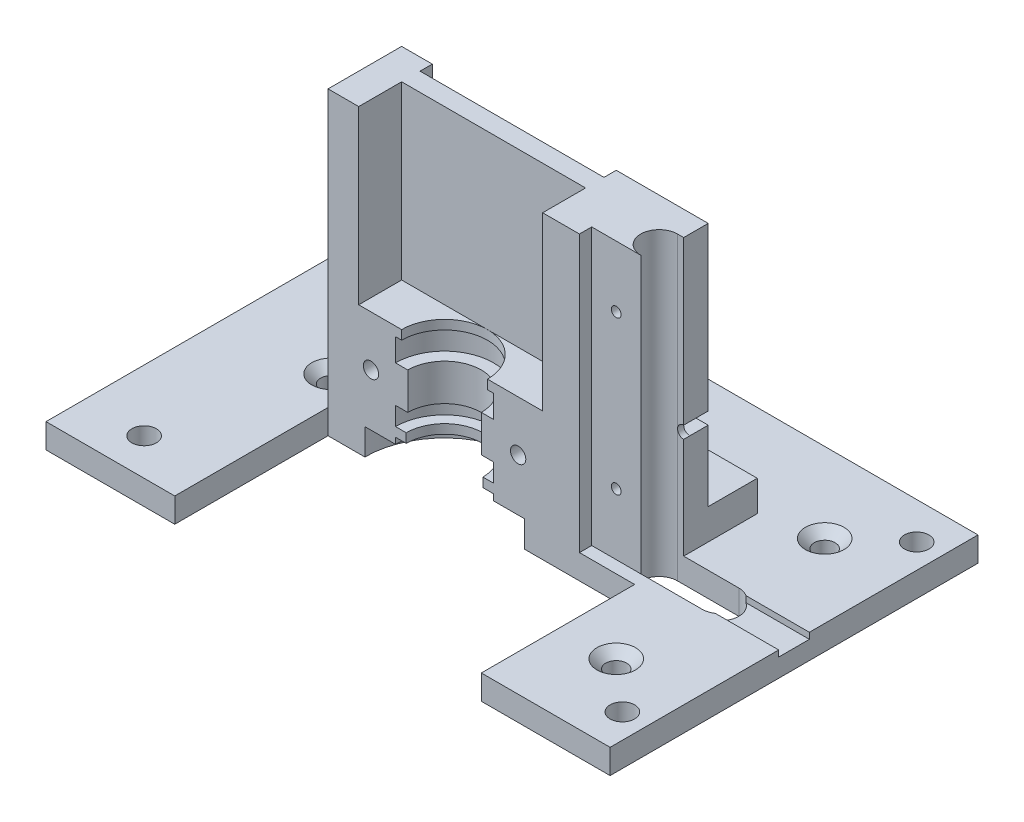
SolidWorks part; units mm, degrees
ref_plane "Front Plane" through (0, 0, 0) normal (0, 0, 1) x (1, 0, 0)
ref_plane "Top Plane" through (0, 0, 0) normal (0, 1, 0) x (1, 0, 0)
ref_plane "Right Plane" through (0, 0, 0) normal (1, 0, 0) x (0, 0, -1)
sketch "Sketch1" plane through (0, 0, 0) normal (0, 1, 0) x (1, 0, 0)
  line L0 (25, -30) -> (46, -30)
  line L1 (-46, -30) -> (-25, -30)
  line L2 (-46, -30) -> (-46, 30)
  line L3 (-46, 30) -> (-25, 30)
  line L4 (46, -30) -> (46, 30)
  line L5 (-46, -30) -> (46, 30) construction
  line L6 (-46, 30) -> (46, -30) construction
  line L8 (-25, -30) -> (-25, -5)
  line L9 (-25, -5) -> (25, -5)
  line L10 (25, -30) -> (25, -5)
  line L11 (-9.5, 30) -> (46, 30)
  line L13 (-25, 30) -> (-25, 25)
  line L14 (-25, 25) -> (-9.5, 25)
  line L15 (-9.5, 30) -> (-9.5, 25)
  point P0 (0, 0)
  dimension "D1" = 60
  dimension "D2" = 92
  dimension "D3" = 25
  dimension "D4" = 50
  dimension "D5" = 21
  dimension "D6" = 15.5
  dimension "D7" = 5
  dimension "D8" = 21
extrude "Boss-Extrude1" add sketch "Sketch1" along normal blind 4
sketch "Sketch2" plane through (0, 4, 0) normal (0, 1, 0) x (1, 0, 0)
  line L1 (-25, -5) -> (25, -5)
  line L2 (-25, -5) -> (-25, 15)
  line L3 (-25, 15) -> (25, 15)
  line L4 (25, -5) -> (25, 15)
  dimension "D1" = 20
  dimension "D2" = 50
extrude "Boss-Extrude2" add sketch "Sketch2" along normal blind 5
sketch "Sketch3" plane through (0, 9, 0) normal (0, 1, 0) x (1, 0, 0)
  line L1 (-25, -5) -> (25, -5)
  line L2 (-25, -5) -> (-25, 7)
  line L3 (-25, 7) -> (25, 7)
  line L4 (25, -5) -> (25, 7)
  dimension "D1" = 12
  dimension "D2" = 50
extrude "Boss-Extrude3" add sketch "Sketch3" along normal blind 40
sketch "Sketch4" plane through (0, 0, -7) normal (0, 0, -1) x (-1, 0, 0)
  line L0 (-25, 49) -> (25, 49) construction
  line L1 (-10, 49) -> (20, 49)
  line L2 (-15, 44) -> (-15, 14)
  line L3 (-10, 9) -> (20, 9)
  line L4 (25, 44) -> (25, 14)
  line L5 (-15, 49) -> (25, 9) construction
  line L6 (-15, 9) -> (25, 49) construction
  line L7 (25, 49) -> (25, 9) construction
  line L11 (-15, 44) -> (-10, 44)
  line L12 (-10, 49) -> (-10, 44)
  line L15 (25, 44) -> (20, 44)
  line L16 (20, 49) -> (20, 44)
  line L19 (-15, 14) -> (-10, 14)
  line L20 (-10, 9) -> (-10, 14)
  line L23 (25, 14) -> (20, 14)
  line L24 (20, 9) -> (20, 14)
  point P0 (5, 29)
  dimension "D1" = 20
  dimension "D2" = 20
  dimension "D3" = 40
  dimension "D4" = 40
  dimension "D5" = 5
  dimension "D6" = 5
  dimension "D7" = 5
  dimension "D8" = 5
  dimension "D9" = 5
  dimension "D10" = 5
  dimension "D11" = 5
  dimension "D12" = 5
  dimension "D13" = 5
  dimension "D14" = 5
  dimension "D15" = 15
  dimension "D16" = 15
  dimension "D17" = 30
  dimension "D18" = 30
extrude "Cut-Extrude1" cut sketch "Sketch4" against normal blind 2
sketch "Sketch5" plane through (0, 0, 5) normal (0, 0, 1) x (1, 0, 0)
  line L0 (-25, 49) -> (25, 49) construction
  line L1 (-20, 49) -> (10, 49)
  line L2 (-20, 49) -> (-20, 21)
  line L3 (-20, 21) -> (10, 21)
  line L4 (10, 49) -> (10, 21)
  line L5 (-25, 49) -> (-25, 4) construction
  dimension "D1" = 28
  dimension "D2" = 30
  dimension "D3" = 5
extrude "Cut-Extrude2" cut sketch "Sketch5" against normal blind 7
ref_plane "Plane1" through (-6, 0, 0) normal (-1, 0, 0) x (0, 0, 1)
sketch "Sketch6" plane through (-6, 0, 0) normal (-1, 0, 0) x (0, 0, 1)
  line L0 (5, 0) -> (5, 21) construction
  line L1 (-30, 0) -> (30, 0) construction
  line L2 (5, 49) -> (5, 4) construction
  line L3 (5, 0) -> (5, 21)
  line L4 (5, 21) -> (-2, 21)
  line L5 (-2, 21) -> (-2, 19.5)
  line L6 (-2, 19.5) -> (-3, 19.5)
  line L7 (-3, 19.5) -> (-3, 15.8)
  line L8 (-3, 15.8) -> (-1, 15.8)
  line L9 (-1, 15.8) -> (-1, 9.8)
  line L10 (-1, 9.8) -> (-3, 9.8)
  line L11 (-3, 9.8) -> (-3, 6.8)
  line L12 (-3, 6.8) -> (-1.25, 6.8)
  line L13 (-1.25, 6.8) -> (-1.25, 5.3)
  line L14 (-1.25, 5.3) -> (-3, 5.3)
  line L15 (-3, 5.3) -> (-3, 4.3)
  line L16 (-3, 4.3) -> (-8, 4.3)
  line L17 (-8, 4.3) -> (-8, 0)
  line L18 (-8, 0) -> (5, 0)
  dimension "D1" = 21
  dimension "D2" = 5
  dimension "D3" = 7
  dimension "D4" = 1.5
  dimension "D5" = 1
  dimension "D6" = 3.7
  dimension "D7" = 2
  dimension "D8" = 6
  dimension "D9" = 2
  dimension "D10" = 3
  dimension "D11" = 1.75
  dimension "D12" = 1.5
  dimension "D13" = 1.75
  dimension "D14" = 1
  dimension "D15" = 5
revolve "Cut-Revolve1" cut sketch "Sketch6" angle 360 about L0
sketch "Sketch7" plane through (0, 0, 0) normal (0, -1, 0) x (1, 0, 0)
  line L0 (46, 30) -> (34, 30) construction
  line L1 (25, 30) -> (46, 30) construction
  line L2 (34, 30) -> (34, 0) construction
  line L3 (34, 0) -> (24, 0) construction
  line L4 (34, -3) -> (24, -3)
  line L5 (34, 3) -> (24, 3)
  arc A0 (34, -3) -> (34, 3) centre (34, 0) ccw
  arc A1 (24, 3) -> (24, -3) centre (24, 0) ccw
  point P5 (29, 0)
  dimension "D4" = 3
  dimension "D5" = 5
  dimension "D1" = 12
  dimension "D2" = 30
  dimension "D3" = 10
extrude "Cut-Extrude3" cut sketch "Sketch7" against normal blind 55
sketch "Sketch8" plane through (0, 0, 5) normal (0, 0, 1) x (1, 0, 0)
  line L1 (25, 49) -> (16, 49)
  line L2 (25, 49) -> (25, 4)
  line L3 (25, 4) -> (16, 4)
  line L4 (16, 49) -> (16, 4)
  dimension "D1" = 45
  dimension "D2" = 9
extrude "Cut-Extrude4" cut sketch "Sketch8" against normal blind 2
sketch "Sketch9" plane through (0, 0, -7) normal (0, 0, -1) x (-1, 0, 0)
  line L0 (-25, 49) -> (-25, 9) construction
  line L1 (-25, 22.5) -> (25, 22.5)
  line L2 (-25, 22.5) -> (-25, 20.5)
  line L3 (-25, 20.5) -> (25, 20.5)
  line L4 (25, 22.5) -> (25, 20.5)
  line L5 (25, 14) -> (25, 44) construction
  line L6 (-46, 4) -> (9.5, 4) construction
  dimension "D1" = 16.5
  dimension "D2" = 2
extrude "Cut-Extrude5" cut sketch "Sketch9" against normal blind 3
sketch "Sketch10" plane through (0, 0, -4) normal (0, 0, -1) x (-1, 0, 0)
  line L0 (-25, 22.5) -> (-25, 20.5) construction
  circle A0 centre (-25, 21.5) radius 1
  dimension "D1" = 2
extrude "Cut-Extrude6" cut sketch "Sketch10" against normal blind 2
sketch "Sketch11" plane through (0, 4, 0) normal (0, 1, 0) x (1, 0, 0)
  line L0 (34, 0) -> (46, 0) construction
  line L1 (46, -30) -> (46, 30) construction
  line L2 (46, 0) -> (46, 2.5) construction
  line L4 (46, 2.5) -> (31, 2.5)
  line L5 (46, 2.5) -> (46, -2.5)
  line L6 (46, -2.5) -> (31, -2.5)
  line L7 (31, 2.5) -> (31, -2.5)
  dimension "D1" = 2.5
  dimension "D2" = 5
  dimension "D3" = 15
extrude "Cut-Extrude7" cut sketch "Sketch11" against normal blind 1
sketch "Sketch12" plane through (0, 9, 0) normal (0, 1, 0) x (1, 0, 0)
  line L1 (-19.25, 14.25) -> (9.25, 14.25)
  line L2 (-19.25, 14.25) -> (-19.25, 5.75)
  line L3 (-19.25, 5.75) -> (9.25, 5.75)
  line L4 (9.25, 14.25) -> (9.25, 5.75)
  line L6 (10, 5) -> (-20, 5) construction
  dimension "D1" = 28.5
  dimension "D2" = 8.5
  dimension "D3" = 0.75
  dimension "D4" = 0.75
extrude "Boss-Extrude4" add sketch "Sketch12" along normal blind 2
sketch "Sketch13" plane through (0, 11, 0) normal (0, 1, 0) x (1, 0, 0)
  line L7 (-19.25, 14.25) -> (-19.25, 5.75) construction
  line L8 (-18.75, 13.75) -> (8.25, 13.75)
  line L9 (-18.75, 13.75) -> (-18.75, 5.75)
  line L10 (-18.75, 5.75) -> (8.25, 5.75)
  line L11 (8.25, 13.75) -> (8.25, 5.75)
  line L12 (9.25, 14.25) -> (-19.25, 14.25) construction
  dimension "D1" = 27
  dimension "D2" = 0.5
  dimension "D3" = 0.5
  dimension "D4" = 8
extrude "Cut-Extrude8" cut sketch "Sketch13" against normal blind 15
sketch "Sketch18" plane through (8.25, 0, 0) normal (-1, 0, 0) x (0, 0, 1)
  line L3 (-7, 4) -> (-7, 0)
  line L12 (-7.75, 5) -> (-7.75, 4)
  line L13 (-7.75, 4) -> (-7, 4)
  line L14 (-30, 0) -> (30, 0) construction
  line L15 (-7, 0) -> (-5.75, 0)
  line L16 (-5.75, 0) -> (-5.75, 9) construction
  line L17 (-5.75, 9) -> (-7.75, 5)
  line L18 (-5.75, 9) -> (-5.75, 0)
  dimension "D1" = 4
  dimension "D2" = 2
  dimension "D4" = 0.75
  dimension "D5" = 4
extrude "Boss-Extrude5" add sketch "Sketch18" along direction (1, 0, 0) on the side of the normal blind 27 contours L15 L18 L17 L12 L13 L3
sketch "Sketch31" plane through (0, 0, 0) normal (0, -1, 0) x (1, 0, 0)
  line L1 (-18.75, -13.75) -> (8.25, -13.75)
  line L2 (-18.75, -13.75) -> (-18.75, -14.5)
  line L3 (-18.75, -14.5) -> (8.25, -14.5)
  line L4 (8.25, -13.75) -> (8.25, -14.5)
  dimension "D1" = 0.75
  dimension "D2" = 27
extrude "Cut-Extrude26" cut sketch "Sketch31" against normal blind 4
ref_plane "Plane3" through (-15, 0, 0) normal (-1, 0, 0) x (0, 0, 1)
sketch "Sketch20" plane through (-15, 0, 0) normal (-1, 0, 0) x (0, 0, 1)
  line L0 (30, 0) -> (-7, 0) construction
  line L1 (-30, 0) -> (30, 0) construction
  line L2 (-7, 0) -> (-7, 2) construction
  line L3 (-7, 0) -> (-14.5, 0) construction
  line L4 (-14.5, 0) -> (-14.5, 2) construction
  line L5 (-14.5, 3) -> (-14.5, 2)
  line L14 (-14.5, 2) -> (-13.5, 2)
  line L15 (-7, 3) -> (-7, 2)
  line L16 (-7, 2) -> (-8, 2)
  line L17 (-7, 2) -> (-14.5, 2) construction
  arc A1 (-13.5, 2) -> (-14.5, 3) centre (-14.5, 2) ccw
  arc A2 (-7, 3) -> (-8, 2) centre (-7, 2) ccw
  dimension "D5" = 2
  dimension "D6" = 2
  dimension "D1" = 37
  dimension "D2" = 2
  dimension "D3" = 7.5
  dimension "D4" = 2
revolve "Revolve1" add sketch "Sketch20" angle 360 about L17
ref_plane "Plane4" through (3, 0, 0) normal (-1, 0, 0) x (0, 0, 1)
sketch "Sketch21" plane through (3, 0, 0) normal (-1, 0, 0) x (0, 0, 1)
  line L0 (30, 0) -> (-7, 0) construction
  line L1 (-30, 0) -> (30, 0) construction
  line L2 (-7, 0) -> (-7, 2) construction
  line L3 (-7, 0) -> (-14.5, 0) construction
  line L4 (-14.5, 0) -> (-14.5, 2) construction
  line L5 (-14.5, 3) -> (-14.5, 2)
  line L6 (-14.5, 2) -> (-13.5, 2)
  line L7 (-7, 3) -> (-7, 2)
  line L8 (-7, 2) -> (-8, 2)
  line L9 (-14.5, 2) -> (-7, 2) construction
  arc A0 (-7, 3) -> (-8, 2) centre (-7, 2) ccw
  arc A1 (-13.5, 2) -> (-14.5, 3) centre (-14.5, 2) ccw
  dimension "D5" = 2
  dimension "D6" = 2
  dimension "D1" = 37
  dimension "D2" = 2
  dimension "D3" = 7.5
  dimension "D4" = 2
revolve "Revolve2" add sketch "Sketch21" angle 360 about L9
sketch "Sketch22" plane through (0, 0, 5) normal (0, 0, 1) x (1, 0, 0)
  line L0 (-25, 0) -> (-19, 0) construction
  line L2 (-25, 49) -> (-25, 4) construction
  line L3 (7, 0) -> (25, 0) construction
  circle A0 centre (6, 12.8) radius 1
  circle A1 centre (-18, 12.8) radius 1
  dimension "D3" = 2
  dimension "D4" = 2
  dimension "D1" = 12.8
  dimension "D5" = 7
  dimension "D2" = 24
  dimension "D6" = 12.8
hole_wizard "M3 Tapped Hole1" positions "3DSketch1" profile "Sketch23" tap size "M3" standard "DIN"
sketch3d "3DSketch1"
  point P0 (-18, 12.8, 5)
  point P3 (6, 12.8, 5)
cosmetic thread "Hole Thread1" parameters "D1"=3.05, "D2"=3
cosmetic thread "Hole Thread2" parameters "D1"=3.05, "D2"=3
sketch "Sketch23" plane through (-18, 12.8, 5) normal (1, 0, 0) x (0, -1, 0)
  line L0 (0, 0) -> (0, 7.7511)
  line L1 (0, 7.7511) -> (1.25, 7)
  line L2 (1.25, 7) -> (1.25, 0)
  line L5 (1.25, 0) -> (0, 0)
  line L10 (0, 7.7511) -> (-1.25, 7) construction
  line L11 (0, -6.35) -> (0, 107.95) construction
  dimension "Tap Drill Dia." = 2.5
  dimension "Tap Drill Depth" = 7
  dimension "Drill Angle" = 118
sketch "Sketch24" plane through (0, 0, 3) normal (0, 0, 1) x (1, 0, 0)
  line L0 (16, 49) -> (20, 49) construction
  line L1 (24, 49) -> (16, 49) construction
  line L2 (20, 49) -> (20, 39) construction
  line L3 (20, 39) -> (20, 14) construction
  dimension "D1" = 4
  dimension "D2" = 10
  dimension "D3" = 25
hole_wizard "M2 Tapped Hole1" positions "3DSketch2" profile "Sketch25" tap size "M2" standard "DIN" end condition through all
sketch3d "3DSketch2"
  point P0 (20, 39, 3)
  point P3 (20, 14, 3)
sketch "Sketch25" plane through (20, 39, 3) normal (1, 0, 0) x (0, -1, 0)
  line L0 (0, 0) -> (0, 33)
  line L1 (0, 33) -> (0.8, 33)
  line L2 (0.8, 33) -> (0.8, 0)
  line L5 (0.8, 0) -> (0, 0)
  line L11 (0, -6.35) -> (0, 107.95) construction
  dimension "Thru Tap Drill Dia." = 1.6
  dimension "Thru Tap Drill Depth" = 33
cosmetic thread "Hole Thread3" parameters "D2"=2
cosmetic thread "Hole Thread4" parameters "D2"=2
sketch "Sketch26" plane through (0, 4, 0) normal (0, 1, 0) x (1, 0, 0)
  line L0 (-25, 30) -> (-46, 30) construction
  line L1 (-46, 30) -> (-46, -30) construction
  circle A0 centre (-36, 24) radius 2
  dimension "D1" = 6
  dimension "D2" = 10
  dimension "D3" = 4
extrude "Cut-Extrude25" cut sketch "Sketch26" against normal blind 5
pattern_linear "LPattern2" count 2 spacing 78 along (1, 0, 0) count 2 spacing 48 along (0, 0, 1) of "Cut-Extrude25"
sketch "Sketch27" plane through (0, 4, 0) normal (0, 1, 0) x (1, 0, 0)
  line L0 (-46, 0) -> (-29.5, 0) construction
  line L1 (-46, 30) -> (-46, -30) construction
  line L2 (-25, 30) -> (-46, 30) construction
  line L3 (46, 17) -> (34, 17) construction
  line L4 (46, 2.5) -> (46, 30) construction
  line L5 (46, 30) -> (-9.5, 30) construction
  line L6 (46, -17) -> (34, -17) construction
  line L7 (46, -30) -> (46, -2.5) construction
  dimension "D1" = 16.5
  dimension "D2" = 30
  dimension "D3" = 12
  dimension "D4" = 13
  dimension "D5" = 12
  dimension "D6" = 34
hole_wizard "CSK for M3 Countersunk Flat Head Screw1" positions "3DSketch3" profile "Sketch28" countersink size "M3" standard "DIN" end condition through all
sketch3d "3DSketch3"
  point P0 (-29.5, 4, 0)
  point P3 (34, 4, -17)
  point P6 (34, 4, 17)
sketch "Sketch28" plane through (-29.5, 4, 0) normal (1, 0, 0) x (0, 0, 1)
  line L0 (0, 0) -> (0, 4)
  line L1 (0, 4) -> (1.7, 4)
  line L2 (1.7, 4) -> (1.7, 1.45)
  line L3 (1.7, 1.45) -> (3.15, 0)
  line L5 (3.15, 0) -> (0, 0)
  line L6 (-1.7, 1.45) -> (-3.15, 0) construction
  line L11 (0, -6.35) -> (0, 107.95) construction
  dimension "Thru Hole Dia." = 3.4
  dimension "Thru Hole Depth" = 4
  dimension "Near C'Sink Dia." = 6.3
  dimension "Near C'Sink Angle" = 90
sketch "Sketch29" plane through (0, 0, -7) normal (0, 0, -1) x (-1, 0, 0)
  line L0 (20, 49) -> (25, 44) construction
  point P4 (22.5, 46.5)
hole_wizard "M2 Tapped Hole2" positions "3DSketch5" profile "Sketch30" tap size "M2" standard "DIN"
sketch3d "3DSketch5"
  point P0 (-22.5, 46.5, -7)
sketch "Sketch30" plane through (-22.5, 46.5, -7) normal (1, 0, 0) x (0, 1, 0)
  line L0 (0, 0) -> (0, 10.4807)
  line L1 (0, 10.4807) -> (0.8, 10)
  line L2 (0.8, 10) -> (0.8, 9.5)
  line L3 (0.8, 9.5) -> (1, 9.5)
  line L5 (1, 9.5) -> (1, 0.025)
  line L6 (1, 0.025) -> (1.025, 0)
  line L7 (1.025, 0) -> (0, 0)
  line L8 (-1, 0.025) -> (-1.025, 0) construction
  line L10 (0, 10.4807) -> (-0.8, 10) construction
  line L11 (0, -6.35) -> (0, 107.95) construction
  dimension "Tap Drill Dia." = 1.6
  dimension "Tap Drill Depth" = 10
  dimension "Thread Major Dia." = 2
  dimension "Thread Depth" = 9.5
  dimension "Near C'Sink Dia." = 2.05
  dimension "Near C'Sink Angle" = 90
  dimension "Drill Angle" = 118
pattern_linear "LPattern3" count 2 spacing 35 along (1, 0, 0) count 2 spacing 35 along (0, -1, 0) of "M2 Tapped Hole2"
fillet "Fillet1" radius 2 4 edges at (-20, 14, -6) (10, 14, -6) (-20, 44, -6) (10, 44, -6)
sketch "Sketch32" plane through (0, 0, 0) normal (0, -1, 0) x (1, 0, 0)
  circle A0 centre (-6, 5) radius 13
extrude "Cut-Extrude27" cut sketch "Sketch32" against normal blind 4.3
